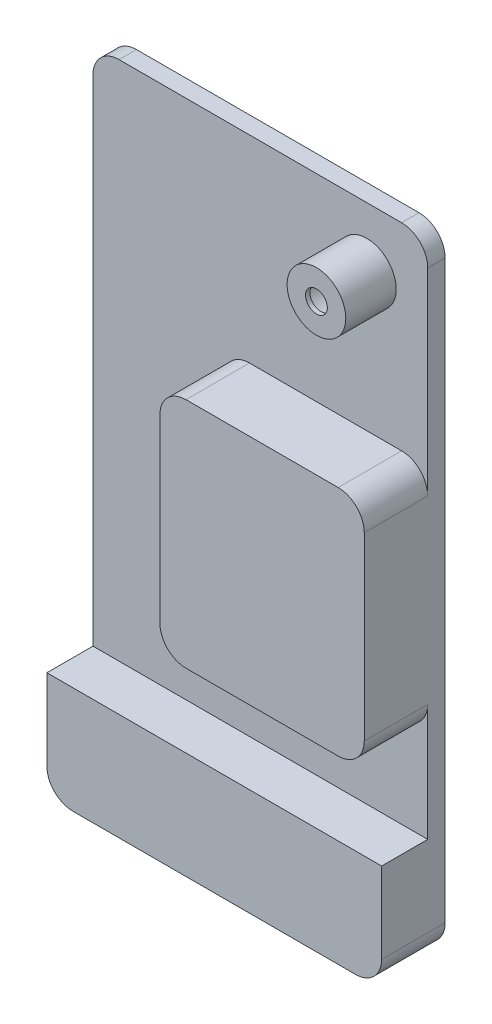
SolidWorks part; units mm, degrees
ref_plane "Ebene vorne" through (0, 0, 0) normal (1, 0, 0) x (0, 1, 0)
ref_plane "Ebene oben" through (0, 0, 0) normal (0, 0, 1) x (0, 1, 0)
ref_plane "Ebene rechts" through (0, 0, 0) normal (0, 1, 0) x (-1, 0, 0)
sketch "Skizze2" plane through (0, 0, 0) normal (0, 0, 1) x (0, 1, 0)
  line L1 (-72.22, -38.5) -> (72.22, -38.5)
  line L2 (-72.22, -38.5) -> (-72.22, 38.5)
  line L3 (-72.22, 38.5) -> (72.22, 38.5)
  line L4 (72.22, -38.5) -> (72.22, 38.5)
  line L5 (-72.22, -38.5) -> (72.22, 38.5) construction
  line L6 (-72.22, 38.5) -> (72.22, -38.5) construction
  point P0 (0, 0)
  dimension "D1" = 77
  dimension "D2" = 144.44
extrude "Aufsatz-Linear austragen1" add sketch "Skizze2" along normal blind 4
sketch "Skizze4" plane through (0, 0, 4) normal (0, 0, 1) x (1, 0, 0)
  line L0 (0, -72.22) -> (0, -61.42) construction
  line L1 (-38.5, -72.22) -> (38.5, -72.22) construction
  line L2 (0, -2.2) -> (0, 2.2) construction
  line L3 (38.5, -72.22) -> (-38.5, -72.22)
  line L4 (38.5, -72.22) -> (38.5, 72.22) construction
  line L6 (-38.5, 72.22) -> (-38.5, -72.22) construction
  line L9 (-38.5, -72.22) -> (-38.5, -47.62)
  line L10 (-38.5, -47.62) -> (38.5, -47.62)
  line L11 (38.5, -72.22) -> (38.5, -47.62)
  dimension "D2" = 24.6
extrude "Aufsatz-Linear austragen2" add sketch "Skizze4" along normal blind 10.6
fillet "Verrundung2" radius 6 4 edges at (-38.5, 72.22, 2) (38.5, 72.22, 2) (38.5, -72.22, 7.3) (-38.5, -72.22, 7.3)
sketch "Skizze5" plane through (0, 0, 4) normal (0, 0, 1) x (1, 0, 0)
  line L1 (38.5, -26.72) -> (-8.5, -26.72)
  line L2 (38.5, -26.72) -> (38.5, 26.78)
  line L3 (38.5, 26.78) -> (-8.5, 26.78)
  line L4 (-8.5, -26.72) -> (-8.5, 26.78)
  line L5 (38.5, -47.62) -> (38.5, 66.22) construction
  line L6 (-32.5, -72.22) -> (32.5, -72.22) construction
  dimension "D1" = 53.5
  dimension "D2" = 47
  dimension "D3" = 45.5
extrude "Aufsatz-Linear austragen3" add sketch "Skizze5" along normal blind 14.6
fillet "Verrundung4" radius 6 4 edges at (38.5, -26.72, 11.3) (-8.5, -26.72, 11.3) (-8.5, 26.78, 11.3) (38.5, 26.78, 11.3)
sketch "Skizze7" plane through (0, 0, 4) normal (0, 0, 1) x (1, 0, 0)
  circle A0 centre (24.5031, 58.3491) radius 6.75
  dimension "D1" = 13.5
extrude "Aufsatz-Linear austragen5" add sketch "Skizze7" along normal blind 11.6
shell "Wandung2" thickness 1
sketch "Skizze8" plane through (0, 0, 15.6) normal (0, 0, 1) x (1, 0, 0)
  circle A0 centre (24.5031, 58.3491) radius 2.5
  dimension "D1" = 5
extrude "Schnitt-Linear austragen1" cut sketch "Skizze8" against normal through all
